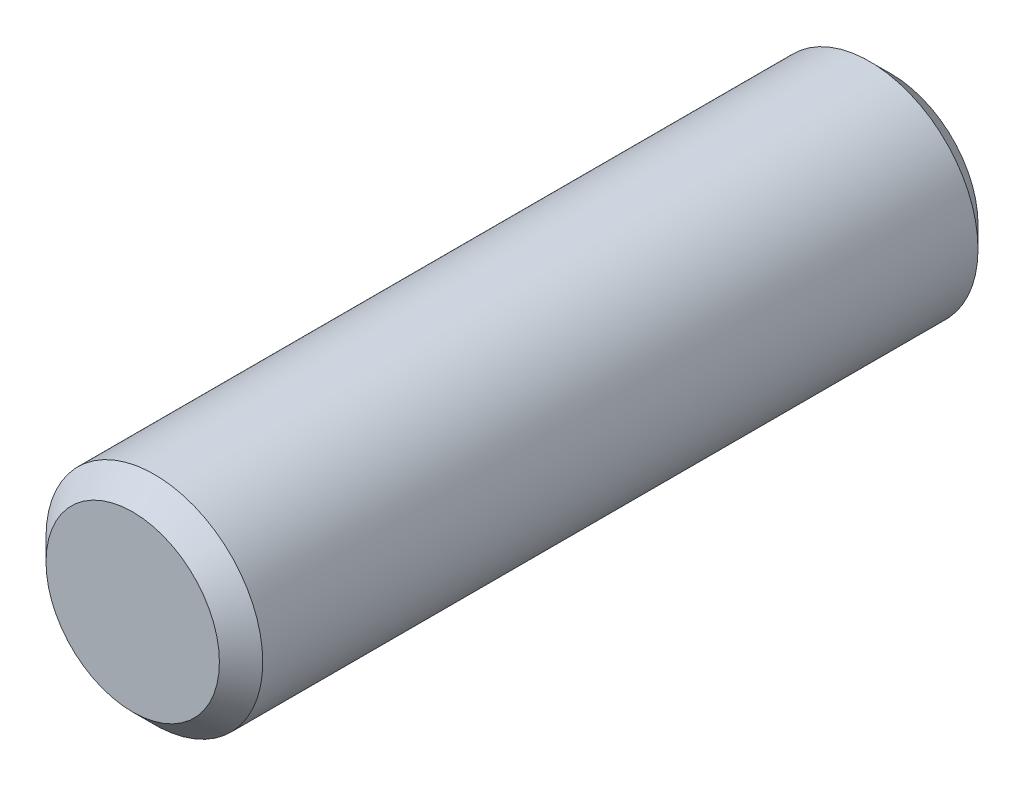
SolidWorks part; units mm, degrees
ref_plane "Ön Düzlem" through (0, 0, 0) normal (0, 0, 1) x (1, 0, 0)
ref_plane "Üst Düzlem" through (0, 0, 0) normal (0, 1, 0) x (1, 0, 0)
ref_plane "Sağ Düzlem" through (0, 0, 0) normal (1, 0, 0) x (0, 0, -1)
sketch "Çizim2" plane through (0, 0, 0) normal (0, 0, 1) x (1, 0, 0)
  circle A0 centre (0, 0) radius 10
  dimension "D1" = 20
extrude "Yükseklik-Ekstrüzyon1" add sketch "Çizim2" along normal mid plane 70
chamfer "Pah1" distance 2 angle 45 2 edges at (10, 0, -35) (10, 0, 35)
